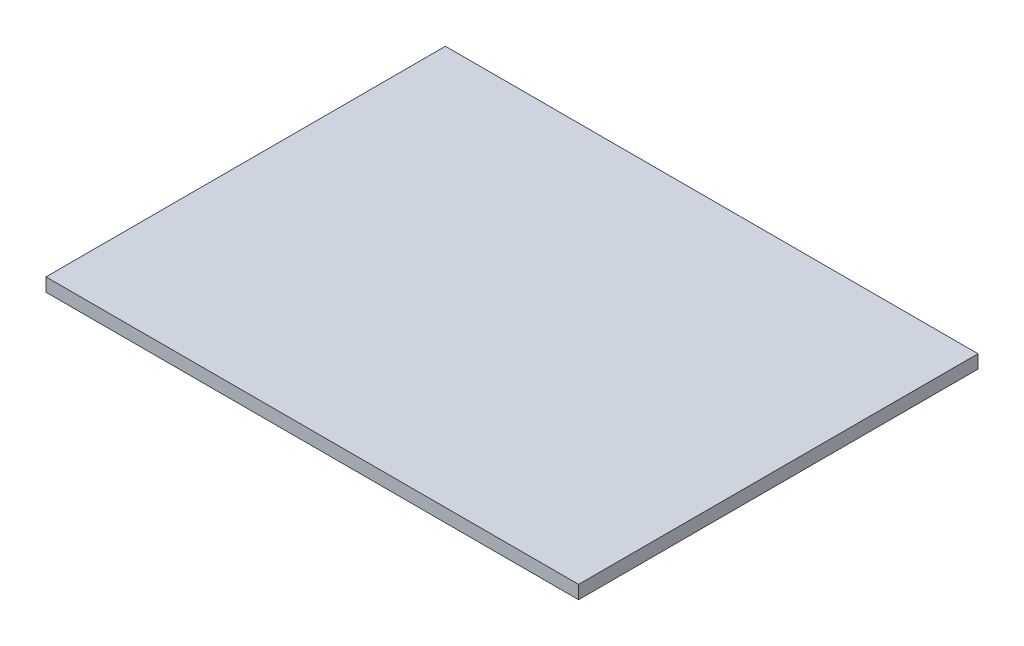
SolidWorks part; units mm, degrees
ref_plane "Front Plane" through (0, 0, 0) normal (0, 0, 1) x (1, 0, 0)
ref_plane "Top Plane" through (0, 0, 0) normal (0, 1, 0) x (1, 0, 0)
ref_plane "Right Plane" through (0, 0, 0) normal (1, 0, 0) x (0, 0, -1)
sketch "Sketch5" plane through (0, 0, 0) normal (0, 0, 1) x (1, 0, 0)
  line L0 (0, 0) -> (0, 50000) construction
sketch "Sketch1" plane through (0, 0, 0) normal (0, 1, 0) x (1, 0, 0)
  line L1 (-100, -75) -> (100, -75)
  line L2 (-100, -75) -> (-100, 75)
  line L3 (-100, 75) -> (100, 75)
  line L4 (100, -75) -> (100, 75)
  line L5 (-100, -75) -> (100, 75) construction
  line L6 (-100, 75) -> (100, -75) construction
  point P0 (0, 0)
  dimension "D1" = 200
  dimension "D2" = 150
extrude "Boss-Extrude1" add sketch "Sketch1" along normal blind 5
sketch "Sketch2" plane through (0, 0, 0) normal (0, 1, 0) x (1, 0, 0)
  line L1 (-30, 0) -> (-15, -25.9808)
  line L2 (-15, -25.9808) -> (15, -25.9808)
  line L3 (15, -25.9808) -> (30, 0)
  line L4 (30, 0) -> (15, 25.9808)
  line L5 (15, 25.9808) -> (-15, 25.9808)
  line L6 (-15, 25.9808) -> (-30, 0)
  circle A0 centre (0, 0) radius 25.9808 construction
  point P1 (0, 25.9808)
  dimension "D1" = 30
extrude "Boss-Extrude2" add sketch "Sketch2" against normal blind 10 separate body
hole_wizard "M3x0.5 Tapped Hole1" positions "Sketch3" profile "Sketch4" tap size "M3x0.5" standard "ANSI Metric"
sketch "Sketch3" plane through (0, 0, 25.9808) normal (0, 0, 1) x (1, 0, 0)
  line L0 (-7, -5) -> (7, -5) construction
  line L2 (-15, -10) -> (-15, 0) construction
  point P0 (-7, -5)
  point P2 (7, -5)
  point P9 (0, -5)
  point P13 (-15, -5)
  dimension "D1" = 8
sketch "Sketch4" plane through (-7, -5, 25.9808) normal (1, 0, 0) x (0, -1, 0)
  line L0 (0, 0) -> (0, 10.7511)
  line L1 (0, 10.7511) -> (1.25, 10)
  line L2 (1.25, 10) -> (1.25, 0)
  line L5 (1.25, 0) -> (0, 0)
  line L10 (0, 10.7511) -> (-1.25, 10) construction
  line L11 (0, -6.35) -> (0, 107.95) construction
  dimension "Tap Drill Dia." = 2.5
  dimension "Tap Drill Depth" = 10
  dimension "Drill Angle" = 118
cosmetic thread "Hole Thread1" parameters "D1"=5, "D2"=3
cosmetic thread "Hole Thread2" parameters "D1"=5, "D2"=3
pattern_circular "CirPattern1" count 3 over 360 about axis through (0, 0, 0) along (0, 1, 0) of "M3x0.5 Tapped Hole1"
cosmetic thread "Hole Thread3" parameters "D1"=5, "D2"=3
cosmetic thread "Hole Thread4" parameters "D1"=5, "D2"=3
cosmetic thread "Hole Thread5" parameters "D1"=5, "D2"=3
cosmetic thread "Hole Thread6" parameters "D1"=5, "D2"=3
